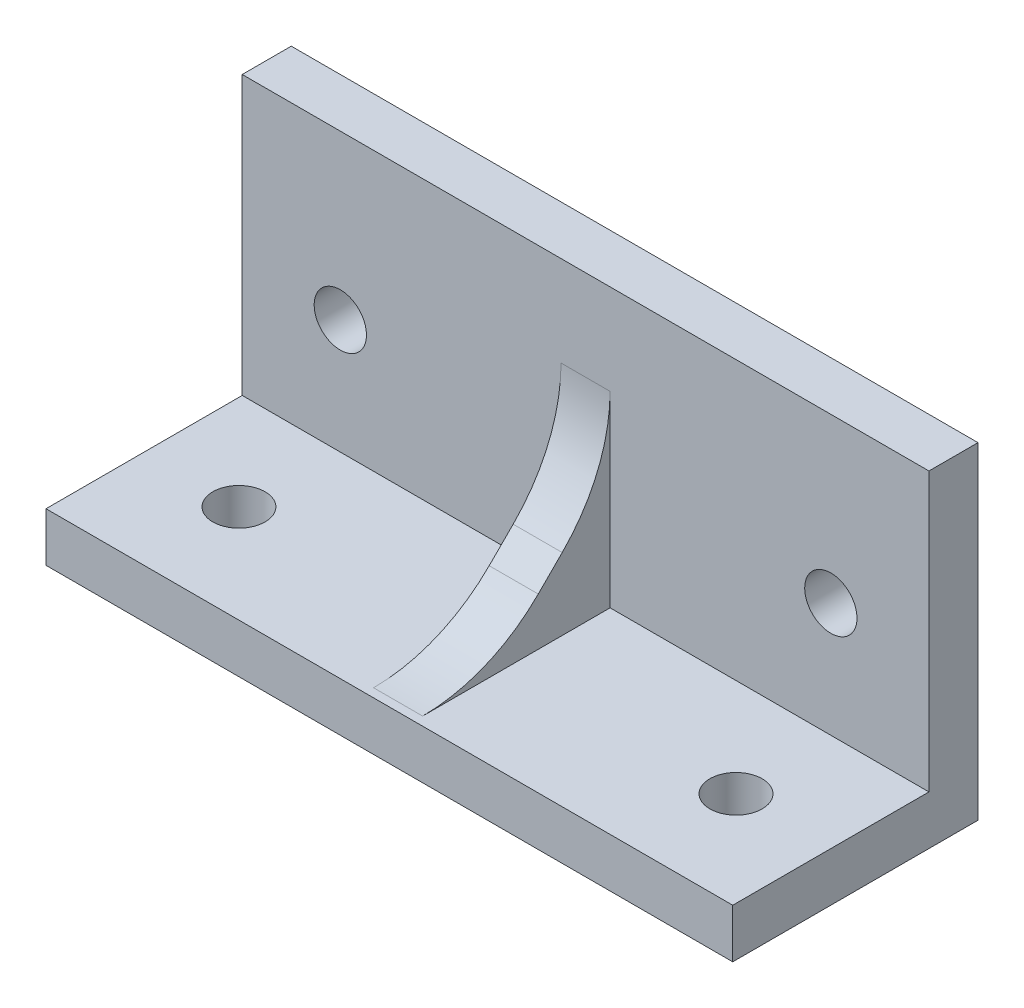
SolidWorks part; units mm, degrees
ref_plane "Front Plane" through (0, 0, 0) normal (0, 0, 1) x (1, 0, 0)
ref_plane "Top Plane" through (0, 0, 0) normal (0, 1, 0) x (1, 0, 0)
ref_plane "Right Plane" through (0, 0, 0) normal (1, 0, 0) x (0, 0, -1)
sketch "Sketch1" plane through (0, 0, 0) normal (0, 0, 1) x (1, 0, 0)
  line L1 (0, 0) -> (42, 0)
  line L2 (0, 0) -> (0, 3)
  line L3 (0, 3) -> (42, 3)
  line L4 (42, 0) -> (42, 3)
  dimension "D1" = 42
  dimension "D2" = 3
extrude "Boss-Extrude1" add sketch "Sketch1" along normal blind 15
sketch "Sketch2" plane through (0, 3, 0) normal (0, 1, 0) x (1, 0, 0)
  line L0 (42, -15) -> (42, 0) construction
  line L1 (0, 0) -> (42, 0)
  line L2 (0, 0) -> (0, -3)
  line L3 (0, -3) -> (42, -3)
  line L4 (42, 0) -> (42, -3)
  dimension "D1" = 3
extrude "Boss-Extrude2" add sketch "Sketch2" along normal blind 17
sketch "Sketch6" plane through (0, 3, 0) normal (0, 1, 0) x (1, 0, 0)
  line L0 (42, -9) -> (0, -9) construction
  line L3 (21, -9) -> (21, -3) construction
  line L4 (0, -3) -> (42, -3) construction
  line L5 (42, -15) -> (42, -3) construction
  circle A0 centre (5.8, -9) radius 1.6
  circle A1 centre (36.2, -9) radius 1.6
  dimension "D1" = 3.2
  dimension "D2" = 30.4
extrude "Cut-Extrude1" cut sketch "Sketch6" against normal up to next
sketch "Sketch7" plane through (0, 0, 0) normal (0, 0, -1) x (-1, 0, 0)
  line L0 (-21, 10) -> (-21, 14.7811) construction
  line L1 (-42, 0) -> (-42, 20) construction
  line L2 (-42, 10) -> (0, 10) construction
  line L3 (0, 20) -> (0, 0) construction
  circle A0 centre (-36, 10) radius 1.6
  circle A1 centre (-6, 10) radius 1.6
  dimension "D1" = 3.2
  dimension "D2" = 30
extrude "Cut-Extrude2" cut sketch "Sketch7" against normal up to next
ref_plane "Plane1" through (21, 0, 0) normal (-1, 0, 0) x (0, 0, 1)
sketch "Sketch9" plane through (21, 0, 0) normal (-1, 0, 0) x (0, 0, 1)
  line L0 (3, 10.324) -> (10.324, 3)
  line L1 (3, 20) -> (3, 3) construction
  line L2 (10.324, 3) -> (3, 3)
  line L3 (3, 3) -> (3, 10.324)
  line L4 (15, 3) -> (3, 3) construction
extrude "Boss-Extrude3" add sketch "Sketch9" along normal mid plane 3
fillet "Fillet1" radius 10 2 edges at (21, 10.324, 3) (21, 3, 10.324)
